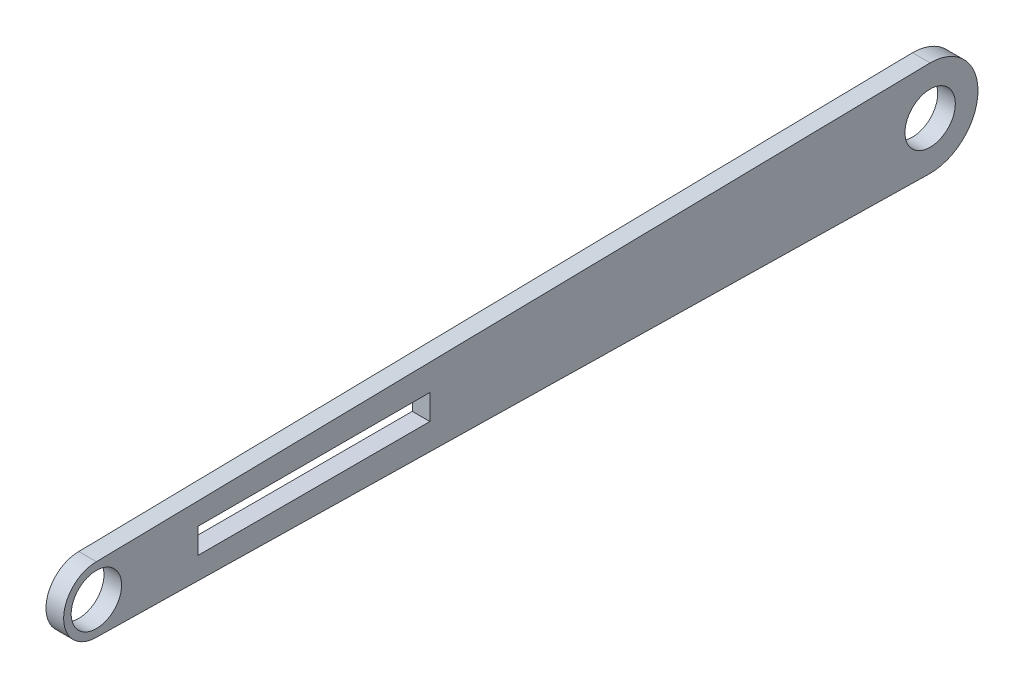
SolidWorks part; units mm, degrees
ref_plane "Front Plane" through (0, 0, 0) normal (0, 0, 1) x (1, 0, 0)
ref_plane "Top Plane" through (0, 0, 0) normal (0, 1, 0) x (1, 0, 0)
ref_plane "Right Plane" through (0, 0, 0) normal (1, 0, 0) x (0, 0, -1)
sketch "Sketch1" plane through (0, 0, 0) normal (1, 0, 0) x (0, 0, -1)
  line L0 (0, 0.65) -> (16.55, 0.95)
  line L1 (16.55, -0.95) -> (0, -0.65)
  line L3 (2.02, 0.25) -> (6.62, 0.25)
  line L4 (2.02, 0.25) -> (2.02, -0.25)
  line L5 (2.02, -0.25) -> (6.62, -0.25)
  line L6 (6.62, 0.25) -> (6.62, -0.25)
  circle A0 centre (0, 0) radius 0.5
  arc A1 (0, 0.65) -> (0, -0.65) centre (0, 0) ccw
  circle A2 centre (16.55, 0) radius 0.5
  arc A3 (16.5156, -0.9494) -> (16.5156, 0.9494) centre (16.55, 0) ccw
  point P15 (2.02, 0)
  dimension "D1" = 16.55
  dimension "D2" = 0.5
  dimension "D3" = 4.6
  dimension "D4" = 2.02
extrude "Boss-Extrude1" add sketch "Sketch1" along normal blind 0.35 contours L1 A3 L0 A1 L3 L6 L5 L4 A0 A2
